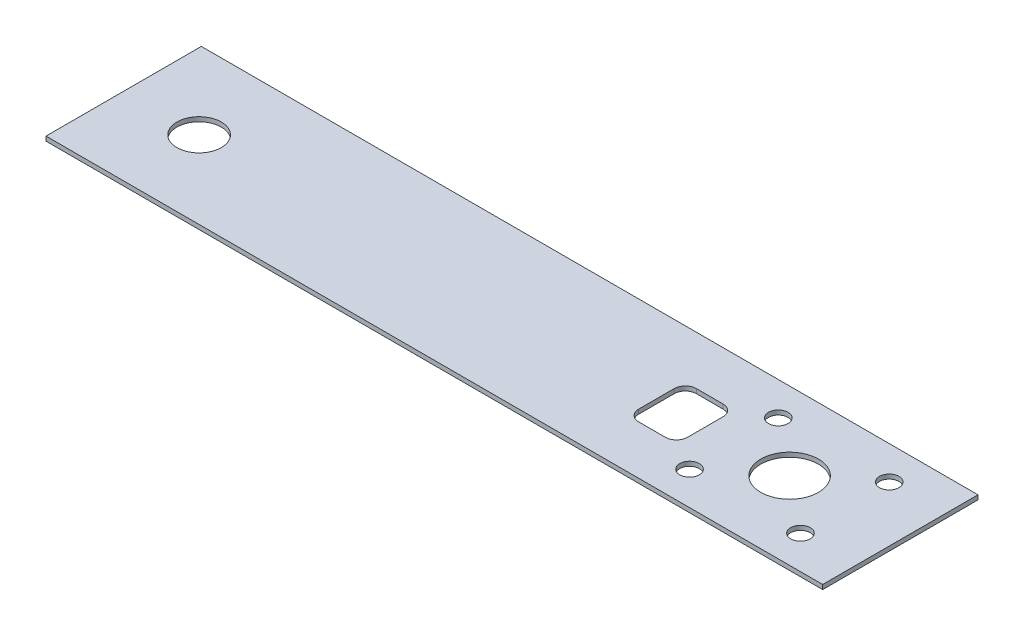
SolidWorks part; units mm, degrees
ref_plane "Front Plane" through (0, 0, 0) normal (0, 0, 1) x (1, 0, 0)
ref_plane "Top Plane" through (0, 0, 0) normal (0, 1, 0) x (1, 0, 0)
ref_plane "Right Plane" through (0, 0, 0) normal (1, 0, 0) x (0, 0, -1)
sketch "Sketch1" plane through (0, 0, 0) normal (0, 1, 0) x (1, 0, 0)
  line L0 (100, 0) -> (150, 0) construction
  line L1 (-175, -35) -> (175, -35)
  line L2 (-175, -35) -> (-175, 35)
  line L3 (-175, 35) -> (175, 35)
  line L4 (175, -35) -> (175, 35)
  line L5 (-175, -35) -> (175, 35) construction
  line L6 (-175, 35) -> (175, -35) construction
  line L7 (150, 20) -> (100, 20) construction
  line L8 (150, 20) -> (150, -20) construction
  line L9 (150, -20) -> (100, -20) construction
  line L10 (100, 20) -> (100, -20) construction
  line L11 (125, 20) -> (125, -20) construction
  line L12 (65.1, 0) -> (87.1, 0) construction
  line L13 (65.1, 8) -> (65.1, 0) construction
  line L14 (82.1, -13) -> (70.1, -13)
  line L15 (87.1, -8) -> (87.1, 8)
  line L16 (82.1, 13) -> (70.1, 13)
  line L17 (65.1, -8) -> (65.1, 8)
  line L18 (87.1, -13) -> (65.1, 13) construction
  line L19 (87.1, 13) -> (65.1, -13) construction
  line L20 (82.1, 13) -> (70.1, 13) construction
  circle A0 centre (150, 20) radius 4.4
  circle A1 centre (150, -20) radius 4.4
  circle A2 centre (100, -20) radius 4.4
  circle A3 centre (100, 20) radius 4.4
  arc A4 (70.1, -13) -> (65.1, -8) centre (70.1, -8) cw
  arc A5 (82.1, -13) -> (87.1, -8) centre (82.1, -8) ccw
  arc A6 (87.1, 8) -> (82.1, 13) centre (82.1, 8) ccw
  arc A7 (70.1, 13) -> (65.1, 8) centre (70.1, 8) ccw
  point P0 (0, 0)
  point P24 (76.1, 0)
  point P25 (76.1, 0)
  dimension "D3" = 5
  dimension "D1" = 70
  dimension "D2" = 350
extrude "Boss-Extrude1" add sketch "Sketch1" along normal blind 2
sketch "Sketch2" plane through (0, 0, 0) normal (0, 1, 0) x (1, 0, 0)
  line L0 (-55, 0) -> (55, 0) construction
  line L1 (175, -35) -> (175, 35) construction
  circle A0 centre (125.1, 0) radius 13
  dimension "D1" = 26
  dimension "D2" = 49.9
extrude "Cut-Extrude1" cut sketch "Sketch2" along normal up to next
sketch "Sketch3" plane through (0, 0, 0) normal (0, 1, 0) x (1, 0, 0)
  line L0 (-55, 0) -> (55, 0) construction
  line L1 (-175, 35) -> (-175, -35) construction
  circle A0 centre (-141, 0) radius 10
  dimension "D1" = 20
  dimension "D2" = 34
extrude "Cut-Extrude2" cut sketch "Sketch3" along normal up to next
